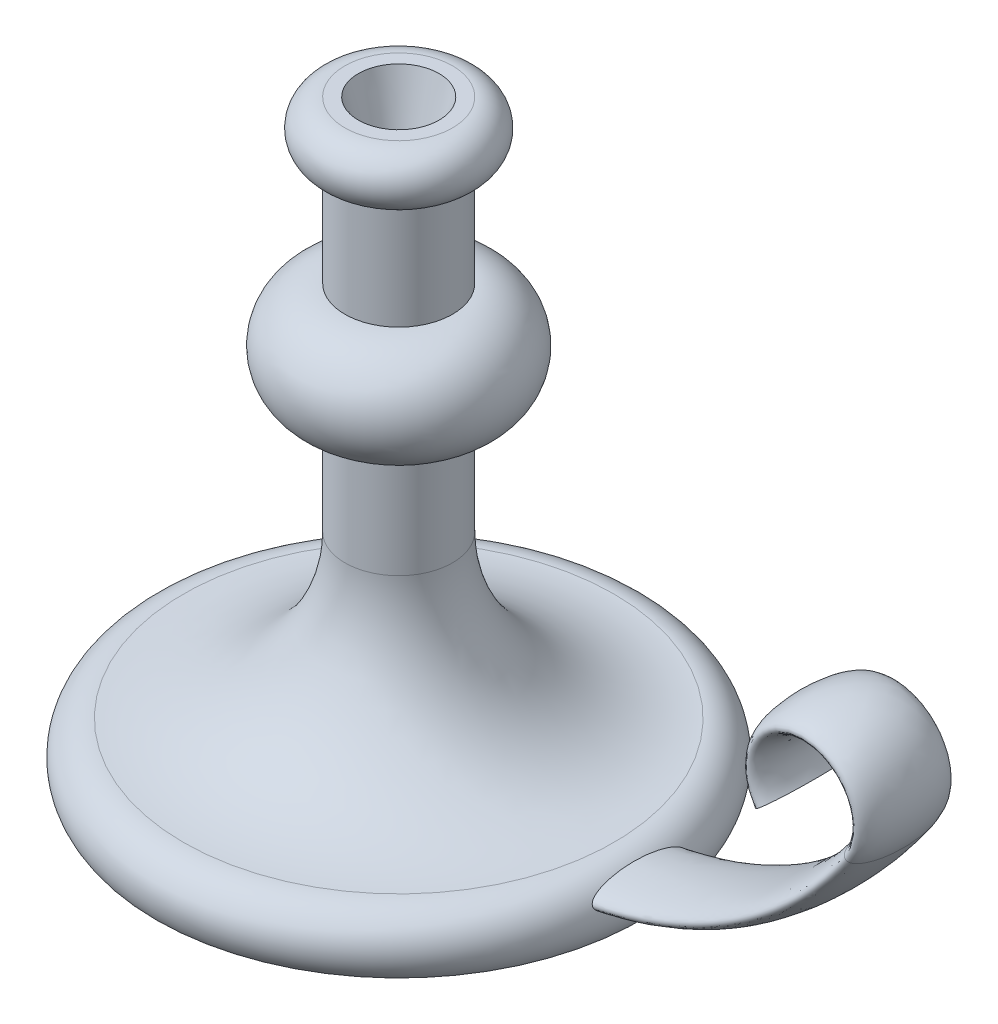
SolidWorks part; units mm, degrees
ref_plane "Front Plane" through (0, 0, 0) normal (0, 0, 1) x (1, 0, 0)
ref_plane "Top Plane" through (0, 0, 0) normal (0, 1, 0) x (1, 0, 0)
ref_plane "Right Plane" through (0, 0, 0) normal (1, 0, 0) x (0, 0, -1)
sketch "Sketch1" plane through (0, 0, 0) normal (0, 0, 1) x (1, 0, 0)
  line L0 (0, 0) -> (0, 220)
  line L1 (0, 0) -> (90, 0)
  line L2 (0, 220) -> (20, 220)
  line L3 (20, 200) -> (20, 160)
  line L4 (20, 120) -> (20, 80)
  arc A0 (20, 220) -> (20, 200) centre (20, 210) cw
  arc A1 (20, 160) -> (20, 120) centre (20, 140) cw
  arc A2 (20, 80) -> (80, 20) centre (80, 80) ccw
  arc A3 (80, 20) -> (90, 0) centre (80, 7.5) cw
  dimension "D4" = 10
  dimension "D5" = 20
  dimension "D7" = 80
  dimension "D1" = 90
  dimension "D2" = 220
  dimension "D3" = 20
  dimension "D6" = 40
revolve "Revolve1" add sketch "Sketch1" angle 360 about L0
sketch "Sketch2" plane through (0, 0, 0) normal (0, 0, 1) x (1, 0, 0)
  line L0 (0, 10) -> (60, 10)
  line L1 (0, 227.4356) -> (0, 175.1288) construction
  line L2 (-90, 0) -> (90, 0) construction
  arc A0 (60, 10) -> (183.5921, 75) centre (60, 160) ccw
  arc A1 (183.5921, 75) -> (150.6342, 75) centre (167.1131, 86.3333) ccw
  dimension "D2" = 150
  dimension "D4" = 20
  dimension "D1" = 60
  dimension "D3" = 65
  dimension "D5" = 10
sketch "Sketch4" plane through (0, 0, 0) normal (1, 0, 0) x (0, 0, -1)
  ellipse E0 centre (0, 10) end of major axis (17.5, 10) minor radius 5
  dimension "D1" = 10
  dimension "D2" = 35
sweep "Sweep1" add profiles "Sketch4" path "Sketch2"
sketch "Sketch5" plane through (0, 220, 0) normal (0, 1, 0) x (1, 0, 0)
  circle A1 centre (0, 0) radius 15
  dimension "D1" = 30
extrude "Cut-Extrude1" cut sketch "Sketch5" against normal blind 25 draft 15 contours A1
